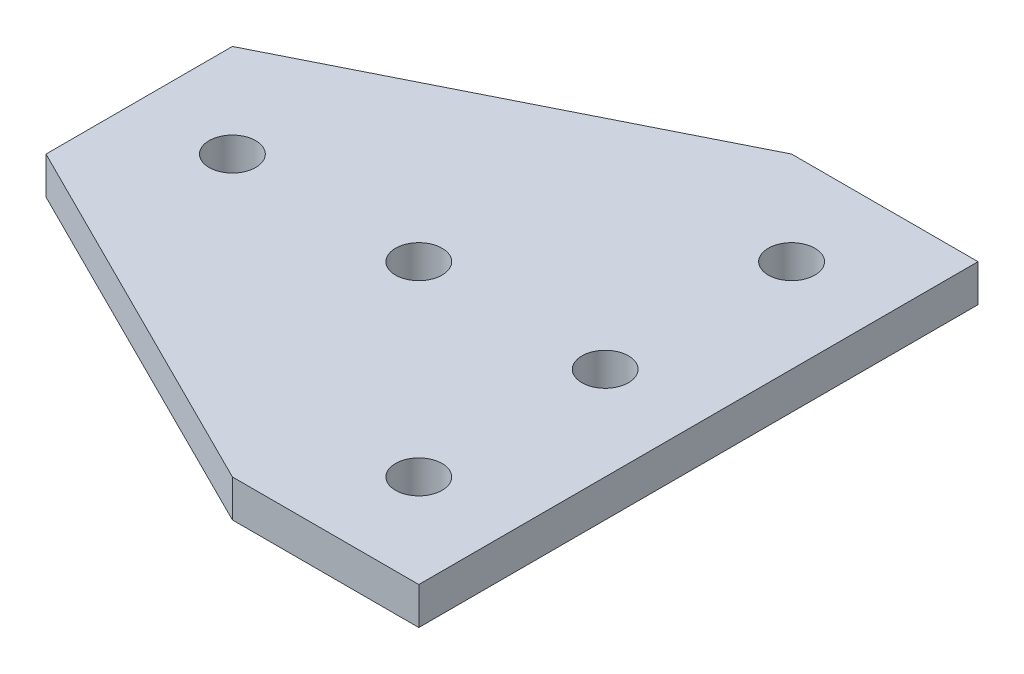
SolidWorks part; units mm, degrees
ref_plane "Front Plane" through (0, 0, 0) normal (0, 0, 1) x (1, 0, 0)
ref_plane "Top Plane" through (0, 0, 0) normal (0, 1, 0) x (1, 0, 0)
ref_plane "Right Plane" through (0, 0, 0) normal (1, 0, 0) x (0, 0, -1)
sketch "Sketch1" plane through (0, 0, 0) normal (0, 1, 0) x (1, 0, 0)
  line L0 (10, 30) -> (10, -30)
  line L1 (10, -30) -> (-10, -30)
  line L2 (-10, -30) -> (-50, -10)
  line L3 (-50, -10) -> (-50, 10)
  line L4 (-50, 10) -> (-10, 30)
  line L5 (-10, 30) -> (10, 30)
  circle A0 centre (0, 0) radius 2.5
  circle A1 centre (0, 20) radius 2.5
  circle A2 centre (0, -20) radius 2.5
  circle A3 centre (-20, 0) radius 2.5
  circle A4 centre (-40, 0) radius 2.5
  point P15 (0, 0)
  point P18 (0, 0)
  point P19 (-23.9907, 6.7502)
  point P20 (19.0212, 27.7828)
  point P21 (17.5685, -32.3224)
  point P22 (-29.1901, 0)
  point P23 (-49.8778, -9.7597)
  dimension "D1" = 5
  dimension "D4" = 20
  dimension "D9" = 20
  dimension "D11" = 10
  dimension "D2" = 20
  dimension "D3" = 60
  dimension "D5" = 20
  dimension "D6" = 20
  dimension "D7" = 60
  dimension "D8" = 20
  dimension "D10" = 10
extrude "Boss-Extrude1" add sketch "Sketch1" along normal blind 4
